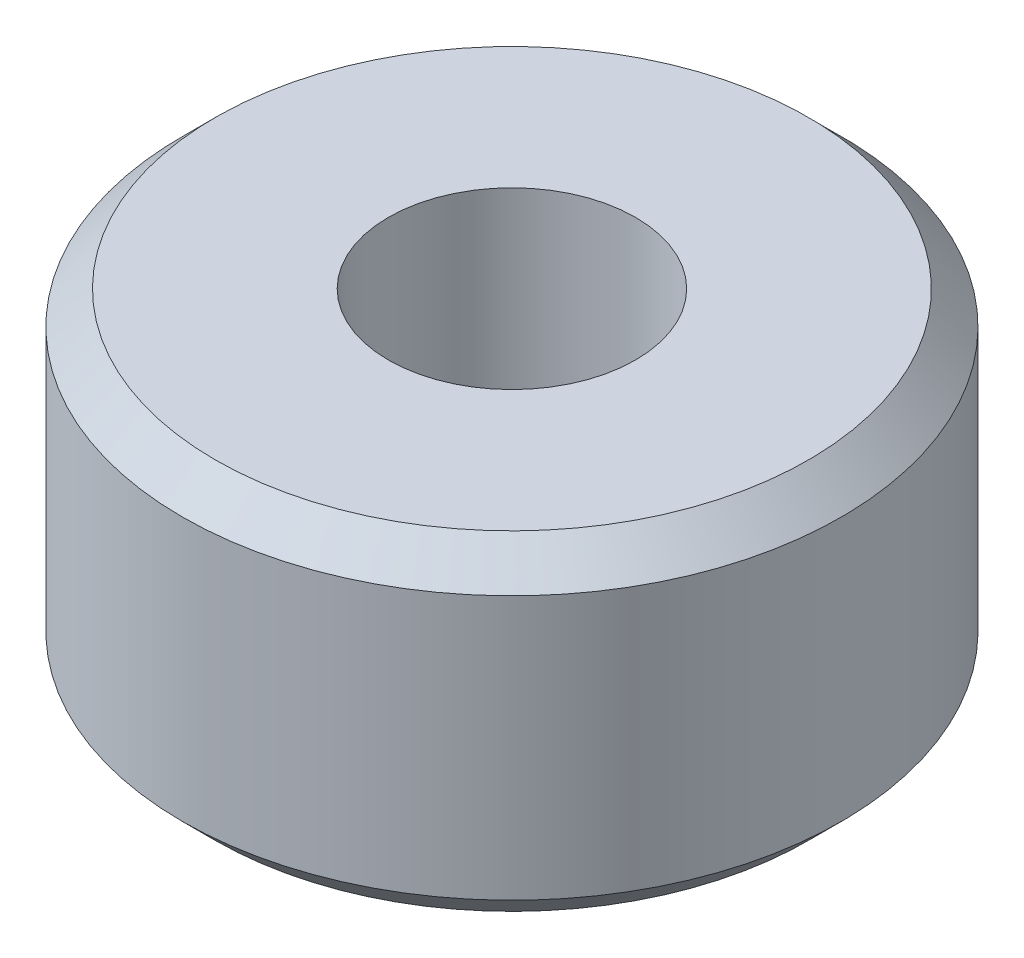
SolidWorks part; units mm, degrees
ref_plane "前视基准面" through (0, 0, 0) normal (0, 0, 1) x (1, 0, 0)
ref_plane "上视基准面" through (0, 0, 0) normal (0, 1, 0) x (1, 0, 0)
ref_plane "右视基准面" through (0, 0, 0) normal (1, 0, 0) x (0, 0, -1)
sketch "草图1" plane through (0, 0, 0) normal (0, 1, 0) x (1, 0, 0)
  circle A0 centre (0, 0) radius 1.5
  circle A1 centre (0, 0) radius 4
  dimension "D1" = 3
  dimension "D2" = 8
extrude "凸台-拉伸1" add sketch "草图1" along normal blind 4
chamfer "倒角1" distance 0.4 angle 45 2 edges at (0, 0, 4) (0, 4, 4)
